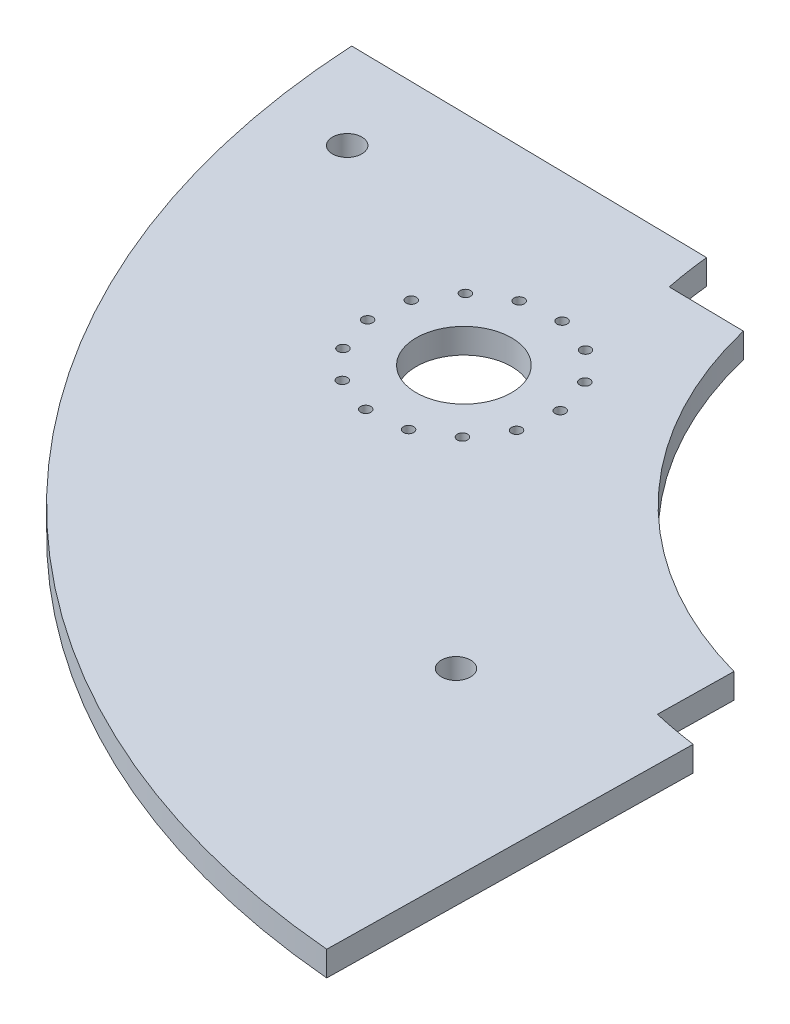
SolidWorks part; units mm, degrees
ref_plane "Front Plane" through (0, 0, 0) normal (0, 0, 1) x (1, 0, 0)
ref_plane "Top Plane" through (0, 0, 0) normal (0, 1, 0) x (1, 0, 0)
ref_plane "Right Plane" through (0, 0, 0) normal (1, 0, 0) x (0, 0, -1)
sketch "Sketch1" plane through (0, 0, 0) normal (0, 1, 0) x (0.9999, 0, 0.016)
  line L1 (-2.9977, -22.8947) -> (-2.9977, -27.431)
  line L2 (-23.7105, -2.1819) -> (-23.1086, -2.1819)
  line L3 (-2.9977, -22.8947) -> (-2.9977, -22.2928)
  line L5 (-53.3584, 0.8181) -> (-28.7544, 0.8181)
  line L6 (-2.9977, -22.8947) -> (-2.9977, -54.0462) construction
  line L7 (0.0023, -27.9386) -> (0.0023, -52.5426)
  line L8 (0.0023, -22.8947) -> (0.0023, -54.0462) construction
  line L10 (-28.2467, -2.1819) -> (-23.7105, -2.1819)
  arc A0 (-2.9977, -27.431) -> (0.0023, -27.9386) centre (4.0023, 4.8181) ccw
  arc A2 (-23.1086, -2.1819) -> (-2.9977, -22.2928) centre (4.0023, 4.8181) ccw
  arc A3 (-28.7544, 0.8181) -> (-28.2467, -2.1819) centre (4.0023, 4.8181) ccw
  arc A4 (-53.3584, 0.8181) -> (0.0023, -52.5426) centre (4.0023, 4.8181) ccw
  circle A32 centre (-27.2644, -8.7557) radius 0.35
  circle A33 centre (-25.3686, -10.6361) radius 0.35
  circle A34 centre (-24.4764, -13.1529) radius 0.35
  circle A35 centre (-24.7645, -15.8076) radius 0.35
  circle A36 centre (-26.1759, -18.0743) radius 0.35
  circle A37 centre (-28.431, -19.5042) radius 0.35
  circle A38 centre (-31.0833, -19.814) radius 0.35
  circle A39 centre (-33.6073, -18.9424) radius 0.35
  circle A40 centre (-35.5031, -17.062) radius 0.35
  circle A41 centre (-36.3953, -14.5452) radius 0.35
  circle A42 centre (-36.1072, -11.8905) radius 0.35
  circle A43 centre (-34.6958, -9.6238) radius 0.35
  circle A44 centre (-32.4406, -8.1939) radius 0.35
  circle A45 centre (-29.7884, -7.8841) radius 0.35
  circle A46 centre (-30.4358, -13.849) radius 3.25
  dimension "D3" = 3
extrude "Boss-Extrude1" add sketch "Sketch1" along normal blind 1.7
extrude "Cut-Extrude9" cut sketch "Sketch10" against normal blind 8 and the other way through all
sketch "Sketch10" plane through (0, -51.287, 0) normal (0, 1, 0) x (0.9999, 0, 0.016)
  circle A0 centre (-13.0987, 51.8027) radius 1
  circle A1 centre (21.1033, 51.8027) radius 1
  circle A2 centre (40.6503, 18.1569) radius 1
  circle A3 centre (55.5443, -5.1203) radius 1
  circle A4 centre (20.5093, -31.747) radius 1
  circle A5 centre (-12.5047, -31.747) radius 1
  circle A6 centre (-47.5397, -5.1203) radius 1
  circle A7 centre (-32.6457, 18.1569) radius 1
